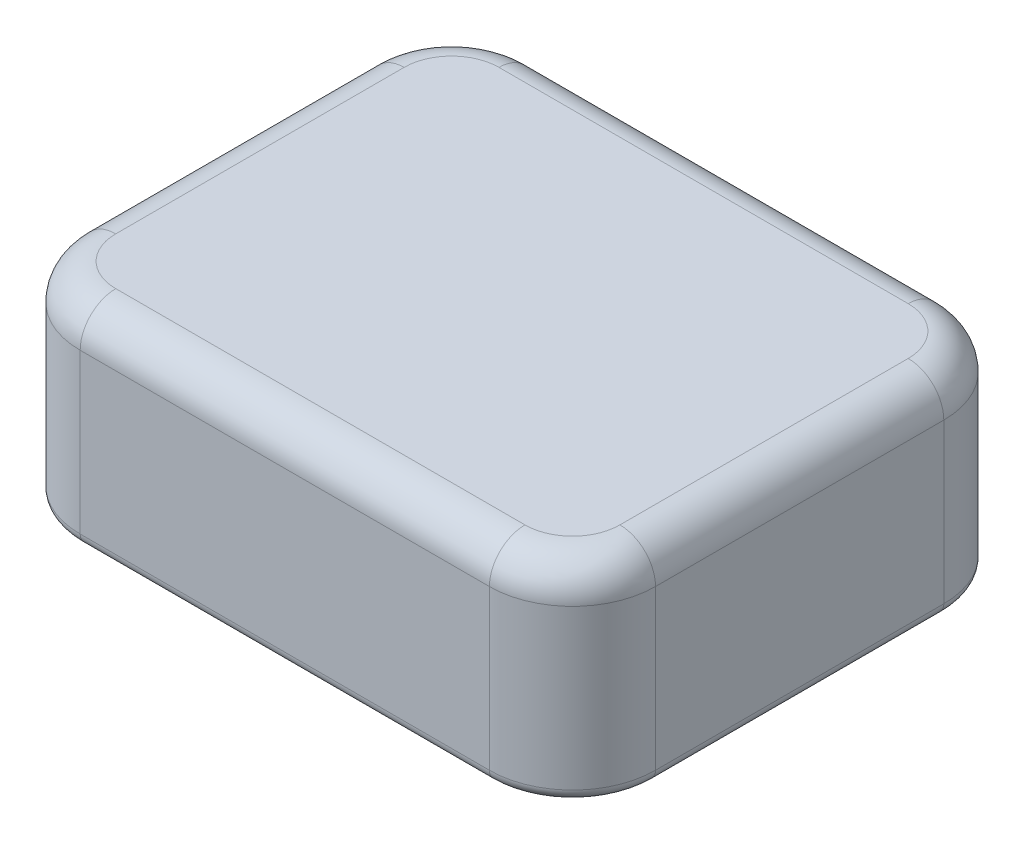
SolidWorks part; units mm, degrees
material "ABS PC"
ref_plane "Front Plane" through (0, 0, 0) normal (0, 0, 1) x (1, 0, 0)
ref_plane "Top Plane" through (0, 0, 0) normal (0, 1, 0) x (1, 0, 0)
ref_plane "Right Plane" through (0, 0, 0) normal (1, 0, 0) x (0, 0, -1)
sketch "Sketch1" plane through (0, 0, 0) normal (0, 1, 0) x (1, 0, 0)
  line L1 (-24.245, -19.15) -> (24.245, -19.15)
  line L2 (-24.245, -19.15) -> (-24.245, 19.15)
  line L3 (-24.245, 19.15) -> (24.245, 19.15)
  line L4 (24.245, -19.15) -> (24.245, 19.15)
  line L5 (-24.245, -19.15) -> (24.245, 19.15) construction
  line L6 (-24.245, 19.15) -> (24.245, -19.15) construction
  point P0 (0, 0)
  dimension "D1" = 48.49
  dimension "D2" = 38.3
extrude "Boss-Extrude1" add sketch "Sketch1" along normal mid plane 17.41
fillet "Fillet1" radius 7 4 edges at (-24.245, 0, -19.15) (24.245, 0, -19.15) (24.245, 0, 19.15) (-24.245, 0, 19.15)
fillet "Fillet2" radius 3 8 edges at (-22.1947, 8.705, 17.0997) (-24.245, 8.705, 0) (-22.1947, 8.705, -17.0997) (0, 8.705, -19.15) (22.1947, 8.705, -17.0997) (24.245, 8.705, 0) (22.1947, 8.705, 17.0997) (0, 8.705, 19.15)
fillet "Fillet3" radius 1 8 edges at (-22.1947, -8.705, 17.0997) (-24.245, -8.705, 0) (-22.1947, -8.705, -17.0997) (0, -8.705, -19.15) (22.1947, -8.705, -17.0997) (24.245, -8.705, 0) (22.1947, -8.705, 17.0997) (0, -8.705, 19.15)
